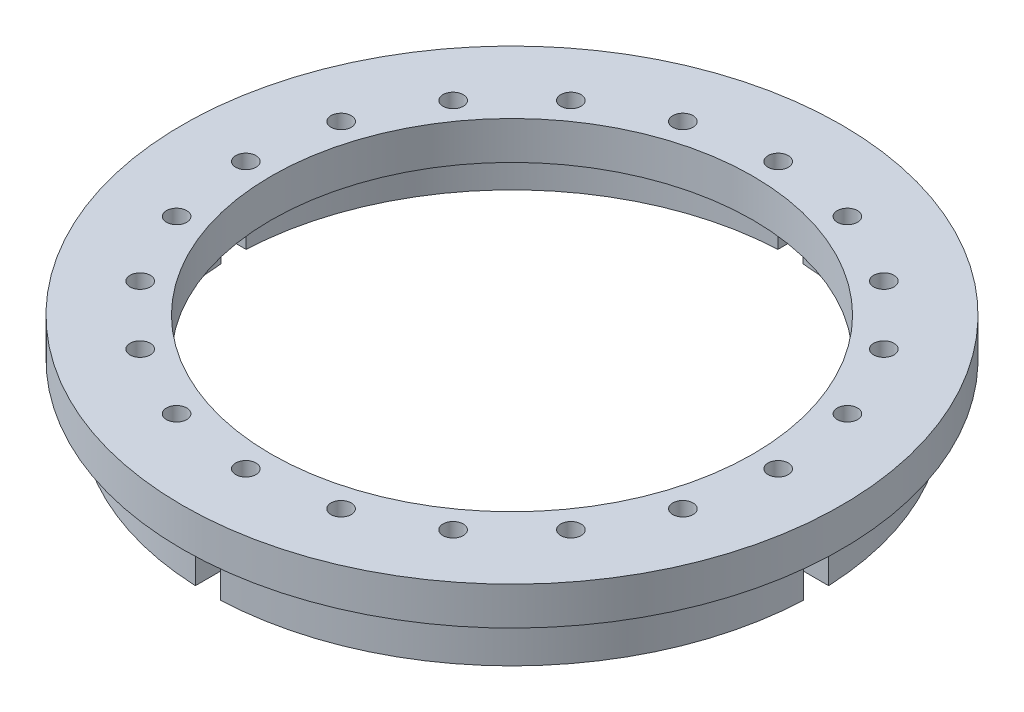
SolidWorks part; units mm, degrees
ref_plane "Front Plane" through (0, 0, 0) normal (0, 0, 1) x (1, 0, 0)
ref_plane "Top Plane" through (0, 0, 0) normal (0, 1, 0) x (1, 0, 0)
ref_plane "Right Plane" through (0, 0, 0) normal (1, 0, 0) x (0, 0, -1)
sketch "Sketch1" plane through (0, 0, 0) normal (0, 1, 0) x (1, 0, 0)
  line L0 (0, 0) -> (19.0013, 0) construction
  circle A0 centre (0, 0) radius 13
  circle A1 centre (0, 0) radius 9.5
  circle A2 centre (10.5, 0) radius 0.4
  circle A3 centre (9.9861, -3.2447) radius 0.4
  circle A4 centre (8.4947, -6.1717) radius 0.4
  circle A5 centre (6.1717, -8.4947) radius 0.4
  circle A6 centre (3.2447, -9.9861) radius 0.4
  circle A7 centre (0, -10.5) radius 0.4
  circle A8 centre (-3.2447, -9.9861) radius 0.4
  circle A9 centre (-6.1717, -8.4947) radius 0.4
  circle A10 centre (-8.4947, -6.1717) radius 0.4
  circle A11 centre (-9.9861, -3.2447) radius 0.4
  circle A12 centre (-10.5, 0) radius 0.4
  circle A13 centre (-9.9861, 3.2447) radius 0.4
  circle A14 centre (-8.4947, 6.1717) radius 0.4
  circle A15 centre (-6.1717, 8.4947) radius 0.4
  circle A16 centre (-3.2447, 9.9861) radius 0.4
  circle A17 centre (0, 10.5) radius 0.4
  circle A18 centre (3.2447, 9.9861) radius 0.4
  circle A19 centre (6.1717, 8.4947) radius 0.4
  circle A20 centre (8.4947, 6.1717) radius 0.4
  circle A21 centre (9.9861, 3.2447) radius 0.4
  point P48 (0, 0)
  dimension "D1" = 26
  dimension "D2" = 19
  dimension "D3" = 0.8
  dimension "D4" = 10.5
  dimension "D5" = 20
extrude "Boss-Extrude1" add sketch "Sketch1" along normal blind 1.5
sketch "Sketch2" plane through (0, 0, 0) normal (0, 1, 0) x (1, 0, 0)
  line L0 (0, -12) -> (0, 12) construction
  line L1 (12, 0) -> (-12, 0) construction
  line L2 (11.9896, 0.5) -> (10.9886, 0.5)
  line L3 (11.9896, -0.5) -> (10.9886, -0.5)
  line L4 (0.5, -11.9896) -> (0.5, -10.9886)
  line L5 (-0.5, -11.9896) -> (-0.5, -10.9886)
  line L6 (-0.5, 10.9886) -> (-0.5, 11.9896)
  line L7 (-10.9886, -0.5) -> (-11.9896, -0.5)
  line L8 (-0.5, -12) -> (-0.5, 12) construction
  line L9 (0.5, 10.9886) -> (0.5, 11.9896)
  line L10 (12, -0.5) -> (-12, -0.5) construction
  line L11 (-10.9886, 0.5) -> (-11.9896, 0.5)
  line L12 (0.5, -12) -> (0.5, 12) construction
  line L14 (12, 0.5) -> (-12, 0.5) construction
  arc A0 (-10.9886, -0.5) -> (-0.5, -10.9886) centre (0, 0) ccw
  arc A1 (11.9896, 0.5) -> (0.5, 11.9896) centre (0, 0) ccw
  arc A2 (-0.5, 11.9896) -> (-11.9896, 0.5) centre (0, 0) ccw
  arc A3 (-11.9896, -0.5) -> (-0.5, -11.9896) centre (0, 0) ccw
  arc A4 (0.5, -11.9896) -> (11.9896, -0.5) centre (0, 0) ccw
  arc A5 (10.9886, 0.5) -> (0.5, 10.9886) centre (0, 0) ccw
  arc A6 (-0.5, 10.9886) -> (-10.9886, 0.5) centre (0, 0) ccw
  arc A7 (0.5, -10.9886) -> (10.9886, -0.5) centre (0, 0) ccw
  point P23 (0, 0)
  dimension "D1" = 22
  dimension "D2" = 24
  dimension "D3" = 0.5
  dimension "D4" = 0.5
  dimension "D5" = 0.5
  dimension "D6" = 0.5
extrude "Boss-Extrude2" add sketch "Sketch2" against normal blind 2
